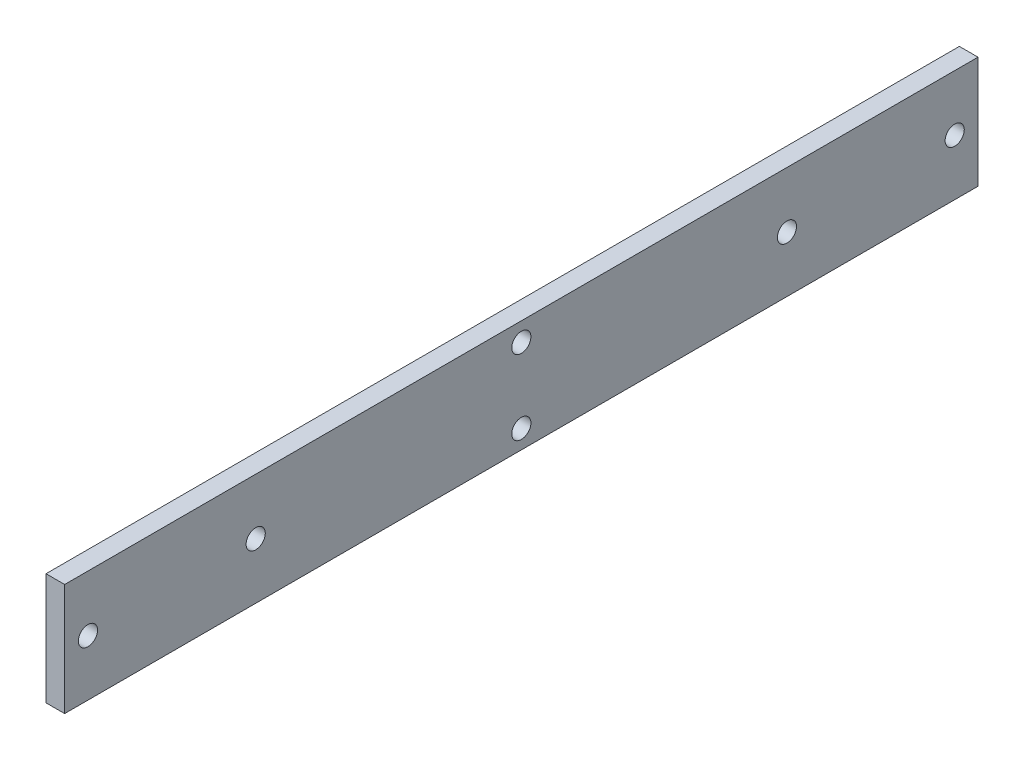
SolidWorks part; units mm, degrees
material "6061-T6 (SS)"
ref_plane "Front" through (0, 0, 0) normal (0, 0, 1) x (1, 0, 0)
ref_plane "Top" through (0, 0, 0) normal (0, 1, 0) x (1, 0, 0)
ref_plane "Right" through (0, 0, 0) normal (1, 0, 0) x (0, 0, -1)
sketch "Sketch1" plane through (0, 0, 0) normal (0, 0, 1) x (1, 0, 0)
  line L1 (-3.175, -19.05) -> (3.175, -19.05)
  line L2 (-3.175, -19.05) -> (-3.175, 19.05)
  line L3 (-3.175, 19.05) -> (3.175, 19.05)
  line L4 (3.175, -19.05) -> (3.175, 19.05)
  line L5 (-3.175, -19.05) -> (3.175, 19.05) construction
  line L6 (-3.175, 19.05) -> (3.175, -19.05) construction
  point P0 (0, 0)
  dimension "D1" = 38.1
  dimension "D2" = 6.35
extrude "Boss-Extrude1" add sketch "Sketch1" along normal mid plane 311.15
sketch "Sketch2" plane through (3.175, 0, 0) normal (1, 0, 0) x (0, 0, -1)
  line L0 (155.575, 0) -> (147.6375, 0) construction
  line L1 (155.575, -19.05) -> (155.575, 19.05) construction
  line L2 (147.6375, 0) -> (90.4875, 0) construction
  line L3 (90.4875, 0) -> (-90.4875, 0) construction
  line L4 (-90.4875, 0) -> (-147.6375, 0) construction
  line L5 (-147.6375, 0) -> (-155.575, 0) construction
  line L6 (-155.575, -19.05) -> (-155.575, 19.05) construction
  line L7 (0, 0) -> (0, 12.7) construction
  line L8 (0, 12.7) -> (0, 19.05) construction
  line L9 (-155.575, 19.05) -> (155.575, 19.05) construction
  line L10 (0, 0) -> (0, -12.7) construction
  line L11 (0, -12.7) -> (0, -19.05) construction
  line L12 (-155.575, -19.05) -> (155.575, -19.05) construction
  point P5 (-119.0625, 0)
  point P12 (119.0625, 0)
  dimension "D1" = 57.15
  dimension "D2" = 238.125
  dimension "D3" = 6.35
hole_wizard "1/4 Clearance Hole1" positions "Sketch4" profile "Sketch3" hole size "1/4" standard "ANSI Inch" end condition through all
sketch "Sketch4" plane through (3.175, 0, 0) normal (1, 0, 0) x (0, 0, -1)
  point P0 (-147.6375, 0)
  point P3 (-90.4875, 0)
  point P6 (90.4875, 0)
  point P9 (147.6375, 0)
  point P12 (0, 12.7)
  point P15 (0, -12.7)
sketch "Sketch3" plane through (3.175, 0, 147.6375) normal (0, 1, 0) x (0, 0, -1)
  line L0 (0, 0) -> (0, 6.35)
  line L1 (0, 6.35) -> (3.2639, 6.35)
  line L2 (3.2639, 6.35) -> (3.2639, 0)
  line L5 (3.2639, 0) -> (0, 0)
  line L11 (0, -6.35) -> (0, 107.95) construction
  dimension "Thru Hole Dia." = 6.5278
  dimension "Thru Hole Depth" = 6.35
